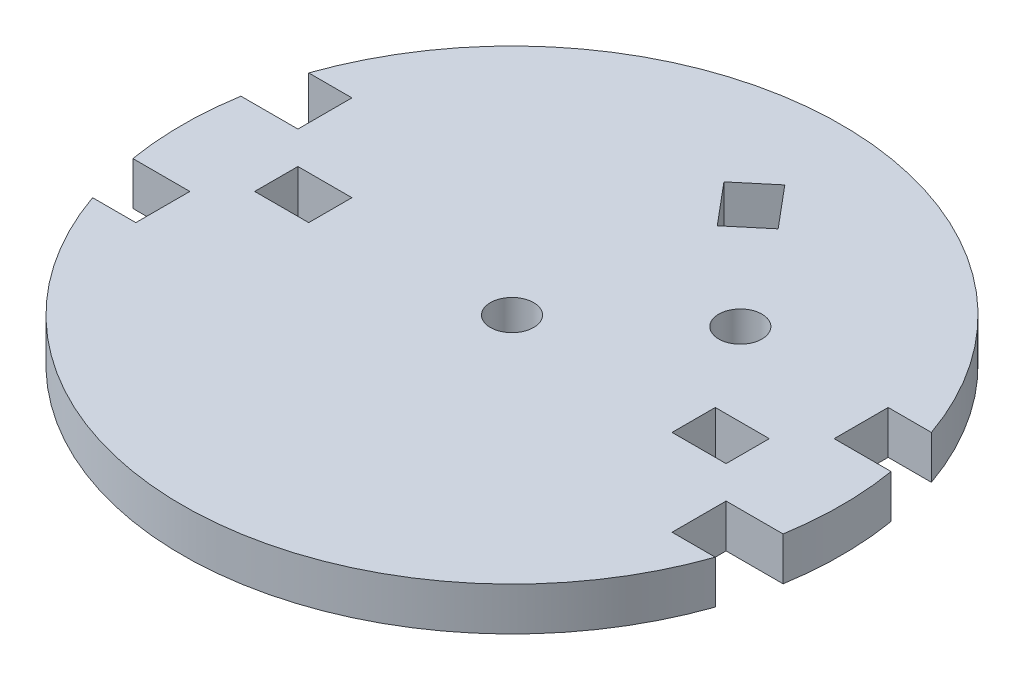
SolidWorks part; units mm, degrees
ref_plane "Alzado" through (0, 0, 0) normal (0, 0, 1) x (1, 0, 0)
ref_plane "Planta" through (0, 0, 0) normal (0, 1, 0) x (1, 0, 0)
ref_plane "Vista lateral" through (0, 0, 0) normal (1, 0, 0) x (0, 0, -1)
sketch "Croquis1" plane through (0, 0, 0) normal (0, 1, 0) x (1, 0, 0)
  circle A0 centre (0, 0) radius 30.5
extrude "Saliente-Extruir1" add sketch "Croquis1" along normal blind 4
sketch "Croquis2" plane through (0, 4, 0) normal (0, 1, 0) x (1, 0, 0)
  circle A0 centre (0, 0) radius 2
extrude "Cortar-Extruir1" cut sketch "Croquis2" against normal blind 4
sketch "Croquis5" plane through (0, 4, 0) normal (0, 1, 0) x (1, 0, 0)
  line L0 (0, 0) -> (0, 10)
  line L1 (28.8141, -5) -> (30.0874, -5)
  line L2 (28.8141, 5) -> (30.0874, 5)
  line L3 (-24.8141, 10) -> (-28.8141, 10)
  line L4 (24.8141, -5) -> (24.8141, -10)
  line L5 (-24.8141, -10) -> (-28.8141, -10)
  line L6 (24.8141, -5) -> (28.8141, -5)
  line L7 (24.8141, 5) -> (24.8141, 10)
  line L8 (-24.8141, 5) -> (-28.8141, 5)
  line L9 (-24.8141, 5) -> (-24.8141, 10)
  line L10 (-24.8141, -5) -> (-28.8141, -5)
  line L11 (-24.8141, -5) -> (-24.8141, -10)
  line L12 (24.8141, 5) -> (28.8141, 5)
  line L13 (24.8141, -10) -> (28.8141, -10)
  line L14 (24.8141, 10) -> (28.8141, 10)
  line L15 (-28.8141, 5) -> (-30.0874, 5)
  line L16 (-28.8141, -5) -> (-30.0874, -5)
  circle A1 centre (0, 0) radius 30.5 construction
  arc A2 (-28.8141, 10) -> (-30.0874, 5) centre (0, 0) ccw
  arc A3 (28.8141, 10) -> (28.8141, -10) centre (0, 0) cw
  arc A4 (-30.0874, -5) -> (-28.8141, -10) centre (0, 0) ccw
  arc A5 (30.0874, -5) -> (28.8141, -10) centre (0, 0) cw
  arc A6 (28.8141, 10) -> (30.0874, 5) centre (0, 0) cw
extrude "Cortar-Extruir3" cut sketch "Croquis5" against normal blind 4
sketch "Croquis6" plane through (0, 4, 0) normal (0, 1, 0) x (1, 0, 0)
  line L8 (-21.8141, 2) -> (-21.8141, -2)
  line L9 (16.8141, 2) -> (21.8141, 2)
  line L10 (16.8141, -2) -> (16.8141, 2)
  line L11 (16.8141, -2) -> (21.8141, -2)
  line L12 (-16.8141, -2) -> (-21.8141, -2)
  line L13 (21.8141, 2) -> (21.8141, -2)
  line L14 (-16.8141, -2) -> (-16.8141, 2)
  line L15 (-16.8141, 2) -> (-21.8141, 2)
extrude "Cortar-Extruir4" cut sketch "Croquis6" against normal blind 4
sketch "Croquis7" plane through (0, 4, 0) normal (0, 1, 0) x (1, 0, 0)
  line L0 (-8.1011, 29.1011) -> (9.5756, 8.0348)
  line L1 (9.5756, 8.0348) -> (27.2522, -13.0314)
  line L2 (-8.1011, 29.1011) -> (-27.2522, 13.0314)
  line L3 (27.2522, -13.0314) -> (8.1011, -29.1011)
  line L4 (8.1011, -29.1011) -> (-27.2522, 13.0314)
  line L5 (2.1944, 23.0542) -> (-0.8697, 20.4831)
  line L6 (2.1944, 23.0542) -> (5.4084, 19.224)
  line L7 (5.4084, 19.224) -> (2.3442, 16.6528)
  line L8 (2.3442, 16.6528) -> (-0.8697, 20.4831)
  circle A0 centre (11.4907, 9.6418) radius 2
  point P7 (-9.5756, -8.0348)
extrude "Cortar-Extruir5" cut sketch "Croquis7" against normal blind 4 contours A0 | L7 L6 L5 L0
